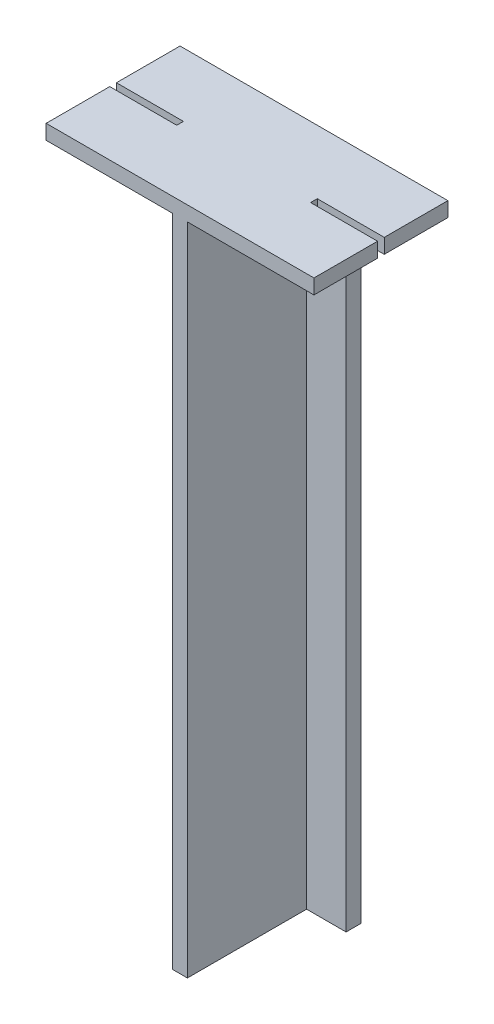
SolidWorks part; units mm, degrees
ref_plane "Plan de face" through (0, 0, 0) normal (0, 0, 1) x (1, 0, 0)
ref_plane "Plan de dessus" through (0, 0, 0) normal (0, 1, 0) x (1, 0, 0)
ref_plane "Plan de droite" through (0, 0, 0) normal (1, 0, 0) x (0, 0, -1)
sketch "Esquisse2" plane through (0, 0, 0) normal (0, 1, 0) x (1, 0, 0)
  line L1 (0, 0) -> (-200, 0)
  line L2 (0, 0) -> (0, 200)
  line L3 (0, 200) -> (-200, 200)
  line L4 (-200, 0) -> (-200, 200)
  line L5 (-200, 95) -> (-100, 95)
  line L6 (-200, 95) -> (-200, 105)
  line L7 (-200, 105) -> (-100, 105)
  line L8 (-100, 95) -> (-100, 105)
  point P9 (-100, 100)
  dimension "D1" = 200
  dimension "D2" = 200
  dimension "D3" = 100
  dimension "D4" = 100
  dimension "D5" = 10
extrude "Boss.-Extru.1" add sketch "Esquisse2" along normal blind 22 contours L8 L5 L4 L1 L2 L3 L7
mirror "Symétrie1" about plane through (0, 22, 0) normal (-1, 0, 0) of "Boss.-Extru.1"
sketch "Esquisse3" plane through (0, 22, 0) normal (0, 1, 0) x (1, 0, 0)
  line L0 (200, 200) -> (-200, 200) construction
  line L1 (-70, 200) -> (70, 200)
  line L2 (-70, 200) -> (-70, 178)
  line L3 (-70, 178) -> (70, 178)
  line L4 (70, 200) -> (70, 178)
  line L5 (-11, 178) -> (11, 178)
  line L6 (-11, 178) -> (-11, 0)
  line L7 (-11, 0) -> (11, 0)
  line L8 (11, 178) -> (11, 0)
  line L9 (200, 0) -> (-200, 0) construction
  point P8 (0, 0)
  point P9 (0, 200)
  point P12 (0, 200)
  point P15 (-70, 189)
  line M6 (-200, 0) -> (200, 0)
  line M12 (200, 200) -> (-200, 200)
  dimension "D1" = 22
  dimension "D2" = 22
  dimension "D3" = 140
extrude "Boss.-Extru.2" add sketch "Esquisse3" against normal blind 1000 contours L4 L2 L3 M12 | L8 L3 L6 M6
